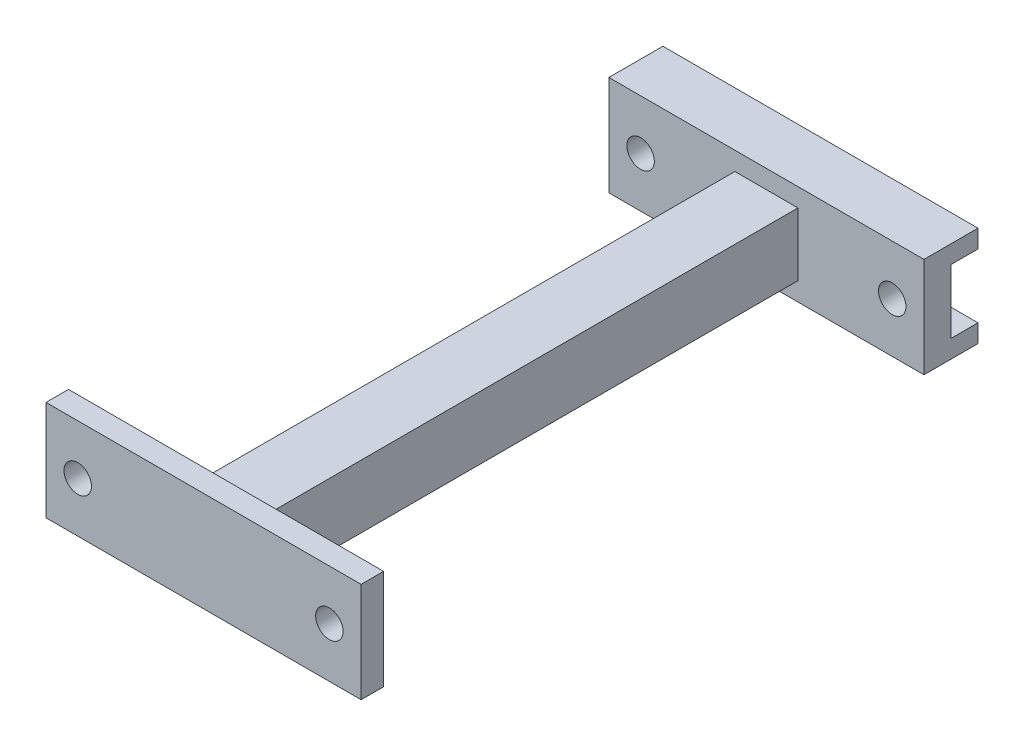
SolidWorks part; units mm, degrees
ref_plane "Front Plane" through (0, 0, 0) normal (0, 0, 1) x (1, 0, 0)
ref_plane "Top Plane" through (0, 0, 0) normal (0, 1, 0) x (1, 0, 0)
ref_plane "Right Plane" through (0, 0, 0) normal (1, 0, 0) x (0, 0, -1)
sketch "Sketch2" plane through (0, 0, 0) normal (0, 0, 1) x (1, 0, 0)
  line L0 (0, 0) -> (27.94, 0) construction
  line L1 (13.97, 0) -> (13.97, -3.55) construction
  line L2 (-3.525, 3.55) -> (31.465, 3.55)
  line L3 (-3.525, 3.55) -> (-3.525, -3.55)
  line L4 (-3.525, -3.55) -> (31.465, -3.55)
  line L5 (31.465, 3.55) -> (31.465, -3.55)
  circle A0 centre (0, 0) radius 1.525
  circle A1 centre (27.94, 0) radius 1.525
  dimension "D2" = 3.05
  dimension "D1" = 27.94
  dimension "D3" = 7.1
  dimension "D4" = 2
extrude "Boss-Extrude1" add sketch "Sketch2" along normal blind 3
sketch "Sketch3" plane through (0, 0, 3) normal (0, 0, 1) x (1, 0, 0)
  line L0 (0, 0) -> (27.94, 0) construction
  line L1 (-3.525, 3.55) -> (-3.525, -3.55) construction
  line L2 (31.465, -3.55) -> (-3.525, -3.55)
  line L3 (31.465, -3.55) -> (31.465, -5.55)
  line L4 (31.465, -5.55) -> (-3.525, -5.55)
  line L5 (-3.525, -3.55) -> (-3.525, -5.55)
  line L6 (-3.525, 3.55) -> (-3.525, 5.55)
  line L7 (31.465, 5.55) -> (-3.525, 5.55)
  line L8 (31.465, 3.55) -> (31.465, 5.55)
  line L9 (31.465, 3.55) -> (-3.525, 3.55)
  dimension "D1" = 2
extrude "Boss-Extrude2" add sketch "Sketch3" against normal blind 6
sketch "Sketch4" plane through (0, 0, 3) normal (0, 0, 1) x (1, 0, 0)
  line L0 (13.97, -5.55) -> (13.97, 5.55) construction
  line L3 (13.97, 0) -> (27.94, 0) construction
  line L4 (10.47, 3.5) -> (17.47, 3.5)
  line L5 (10.47, 3.5) -> (10.47, -3.5)
  line L6 (10.47, -3.5) -> (17.47, -3.5)
  line L7 (17.47, 3.5) -> (17.47, -3.5)
  line L9 (-3.525, -5.55) -> (31.465, -5.55) construction
  dimension "D1" = 7
extrude "Boss-Extrude3" add sketch "Sketch4" along normal blind 60
sketch "Sketch5" plane through (0, 0, 63) normal (0, 0, 1) x (1, 0, 0)
  line L4 (-3.525, 5.55) -> (-3.525, -5.55)
  line L5 (-3.525, 5.55) -> (-3.525, -5.55)
  line L6 (-3.525, -5.55) -> (31.465, -5.55)
  line L7 (-3.525, -5.55) -> (31.465, -5.55)
  line L8 (31.465, -5.55) -> (31.465, 5.55)
  line L9 (31.465, -5.55) -> (31.465, 5.55)
  line L10 (31.465, 5.55) -> (-3.525, 5.55)
  line L11 (31.465, 5.55) -> (-3.525, 5.55)
  circle A0 centre (0, 0) radius 1.525 construction
  circle A1 centre (27.94, 0) radius 1.525 construction
  circle A2 centre (0, 0) radius 1.525
  circle A3 centre (27.94, 0) radius 1.525
  dimension "D1" = 0
extrude "Boss-Extrude4" add sketch "Sketch5" along normal blind 2.5
